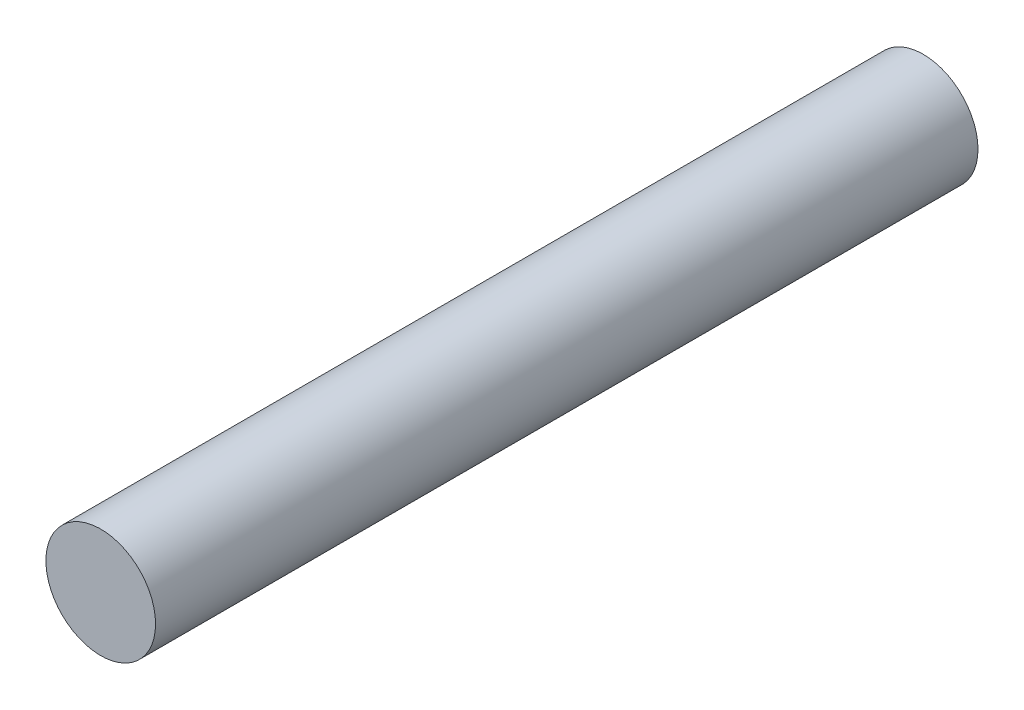
SolidWorks part; units mm, degrees
material "ｽﾃﾝﾚｽ鋼(ｸﾛﾑ)"
ref_plane "正面" through (0, 0, 0) normal (0, 0, 1) x (1, 0, 0)
ref_plane "平面" through (0, 0, 0) normal (0, 1, 0) x (1, 0, 0)
ref_plane "右側面" through (0, 0, 0) normal (1, 0, 0) x (0, 0, -1)
sketch "ｽｹｯﾁ1" plane through (0, 0, 0) normal (0, 0, 1) x (1, 0, 0)
  circle A0 centre (0, 0) radius 2
  dimension "D1" = 4
extrude "ﾎﾞｽ - 押し出し1" add sketch "ｽｹｯﾁ1" along normal blind 30
